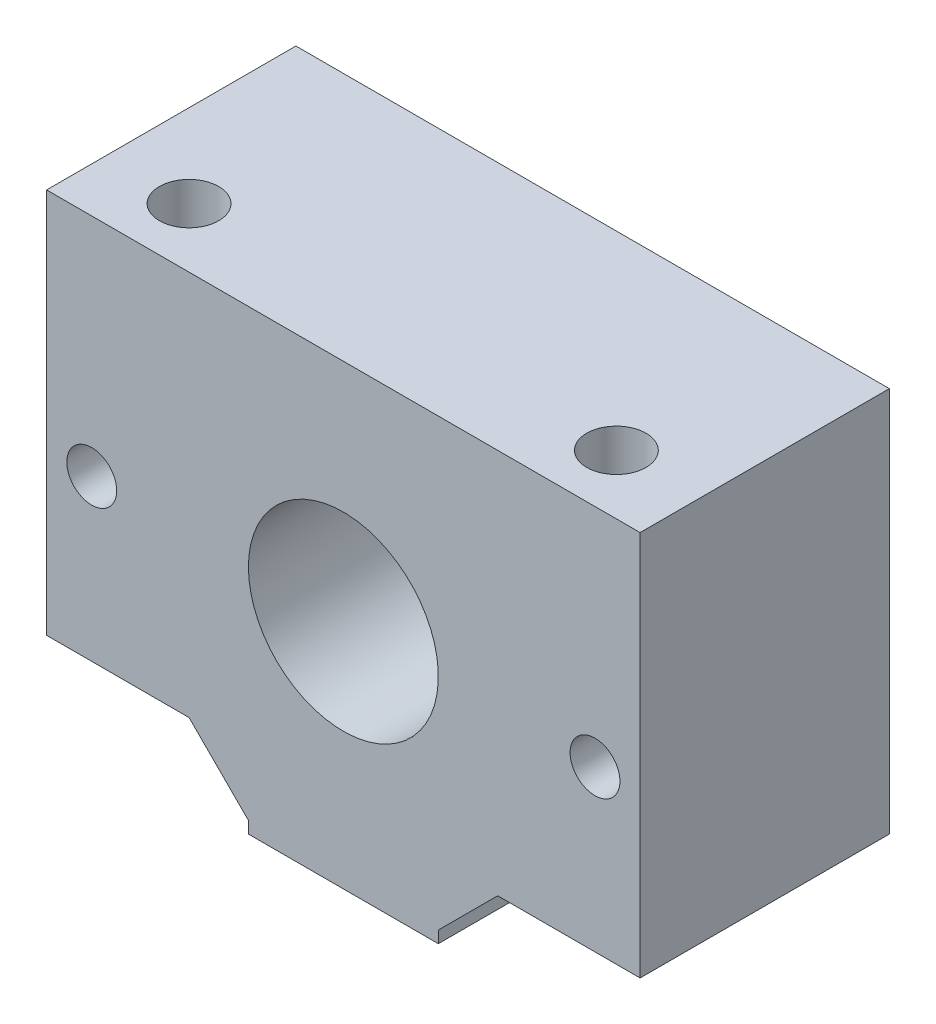
SolidWorks part; units mm, degrees
ref_plane "前视基准面" through (0, 0, 0) normal (0, 0, 1) x (1, 0, 0)
ref_plane "上视基准面" through (0, 0, 0) normal (0, 1, 0) x (1, 0, 0)
ref_plane "右视基准面" through (0, 0, 0) normal (1, 0, 0) x (0, 0, -1)
sketch "草图1" plane through (0, 0, 0) normal (0, 0, 1) x (1, 0, 0)
  line L0 (8, 0) -> (-8, 0)
  line L1 (-8, 0) -> (-8, 1)
  line L2 (-13, 6) -> (-25, 6)
  line L3 (-25, 6) -> (-25, 38.5)
  line L4 (-25, 38.5) -> (25, 38.5)
  line L5 (-8, 1) -> (-13, 6)
  line L6 (0, 0) -> (0, 38.5) construction
  line L7 (8, 1) -> (13, 6)
  line L8 (25, 6) -> (25, 38.5)
  line L9 (13, 6) -> (25, 6)
  line L10 (8, 0) -> (8, 1)
  circle A0 centre (0, 19.5) radius 8
  point P3 (-8, 6)
  point P16 (8, 6)
  dimension "D3" = 16
  dimension "D1" = 25
  dimension "D2" = 38.5
  dimension "D4" = 19
  dimension "D5" = 32.5
  dimension "D6" = 12
extrude "凸台-拉伸1" add sketch "草图1" along normal blind 21
hole_wizard "M5 螺纹孔1" positions "草图4" profile "草图3" tap size "M5" standard "Gb" end condition through all
sketch "草图4" plane through (0, 0, 21) normal (0, 0, 1) x (1, 0, 0)
  line L0 (-25, 38.5) -> (-25, 6) construction
  line L1 (25, 6) -> (25, 38.5) construction
  line L2 (25, 38.5) -> (-25, 38.5) construction
  point P0 (-21.2, 19.5)
  point P2 (21.2, 19.5)
  dimension "D1" = 3.8
  dimension "D2" = 3.8
  dimension "D3" = 19
sketch "草图3" plane through (-21.2, 19.5, 21) normal (1, 0, 0) x (0, -1, 0)
  line L0 (0, 0) -> (0, 21)
  line L1 (0, 21) -> (2.1, 21)
  line L2 (2.1, 21) -> (2.1, 0)
  line L5 (2.1, 0) -> (0, 0)
  line L11 (0, -6.35) -> (0, 107.95) construction
  dimension "通孔螺纹孔钻头直径" = 4.2
  dimension "通孔螺纹孔钻头深度" = 21
cosmetic thread "孔螺蚊线1" parameters "D2"=5
cosmetic thread "孔螺蚊线2" parameters "D2"=5
hole_wizard "Ø5.0 (5) 直径孔1" positions "草图6" profile "草图5" hole size "Ø5.0" standard "Gb" end condition through all
sketch "草图6" plane through (0, 38.5, 0) normal (0, 1, 0) x (1, 0, 0)
  line L0 (-25, -21) -> (-25, 0) construction
  line L1 (25, -21) -> (-25, -21) construction
  line L2 (25, -21) -> (25, 0) construction
  point P0 (-18, -16)
  point P2 (18, -16)
  dimension "D1" = 7
  dimension "D2" = 5
  dimension "D3" = 7
sketch "草图5" plane through (-18, 38.5, 16) normal (1, 0, 0) x (0, 0, 1)
  line L0 (0, 0) -> (0, 38.5)
  line L1 (0, 38.5) -> (2.5, 38.5)
  line L2 (2.5, 38.5) -> (2.5, 0)
  line L5 (2.5, 0) -> (0, 0)
  line L11 (0, -6.35) -> (0, 107.95) construction
  dimension "通孔孔直径" = 5
  dimension "通孔孔深度" = 38.5
